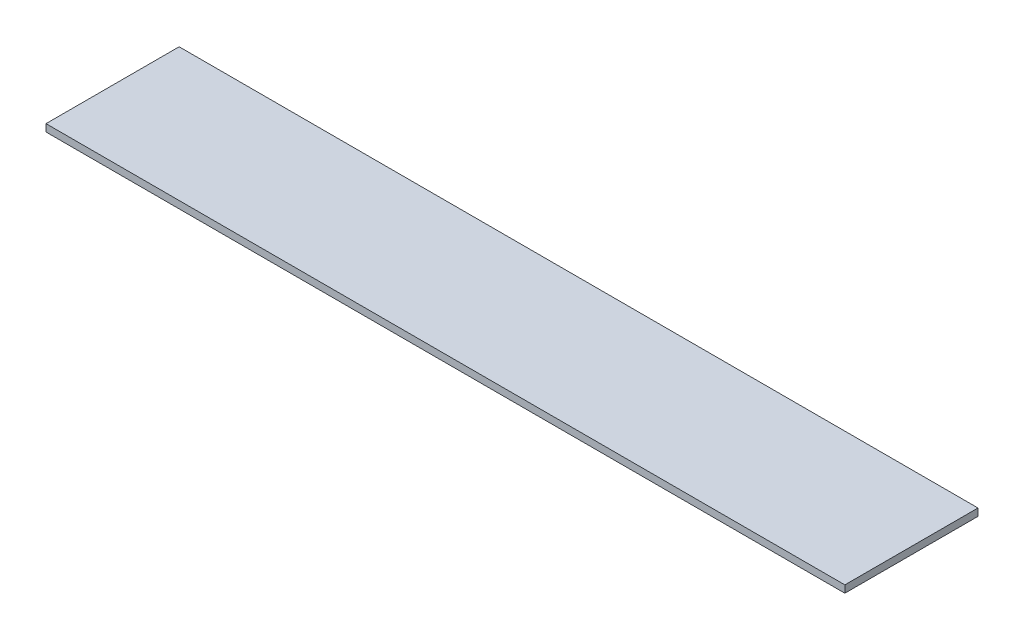
SolidWorks part; units mm, degrees
material "Custom Plastic"
ref_plane "Front Plane" through (0, 0, 0) normal (0, 0, 1) x (1, 0, 0)
ref_plane "Top Plane" through (0, 0, 0) normal (0, 1, 0) x (1, 0, 0)
ref_plane "Right Plane" through (0, 0, 0) normal (1, 0, 0) x (0, 0, -1)
sketch "Sketch1" plane through (0, 0, 0) normal (0, 1, 0) x (1, 0, 0)
  line L1 (0, 0) -> (838.2, 0)
  line L2 (0, 0) -> (0, 139.7)
  line L3 (0, 139.7) -> (838.2, 139.7)
  line L4 (838.2, 0) -> (838.2, 139.7)
  dimension "D1" = 139.7
  dimension "D2" = 838.2
extrude "Boss-Extrude1" add sketch "Sketch1" along normal blind 7.62
